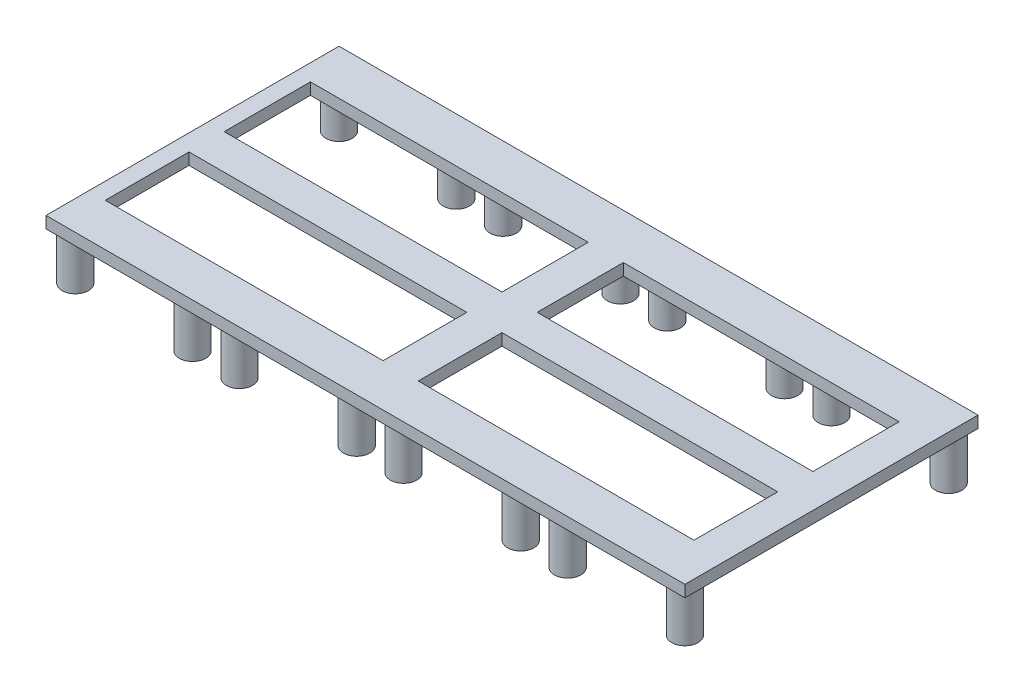
SolidWorks part; units mm, degrees
ref_plane "前视基准面" through (0, 0, 0) normal (0, 0, 1) x (1, 0, 0)
ref_plane "上视基准面" through (0, 0, 0) normal (0, 1, 0) x (1, 0, 0)
ref_plane "右视基准面" through (0, 0, 0) normal (1, 0, 0) x (0, 0, -1)
other "Configuration Table"
sketch "草图1" plane through (0, 0, 0) normal (0, 1, 0) x (1, 0, 0)
  line L1 (-14.9137, 39.4207) -> (10.0863, 39.4207)
  line L2 (-14.9137, 39.4207) -> (-14.9137, -10.5793)
  line L3 (-14.9137, -10.5793) -> (10.0863, -10.5793)
  line L4 (10.0863, 39.4207) -> (10.0863, -10.5793)
  line L5 (-14.9137, 39.4207) -> (10.0863, -10.5793) construction
  line L6 (-14.9137, -10.5793) -> (10.0863, 39.4207) construction
  line L7 (-12.4137, 36.9207) -> (7.5863, 36.9207)
  line L8 (-12.4137, 36.9207) -> (-12.4137, -8.0793)
  line L9 (-12.4137, -8.0793) -> (7.5863, -8.0793)
  line L10 (7.5863, 36.9207) -> (7.5863, -8.0793)
  line L11 (-12.4137, 36.9207) -> (7.5863, -8.0793) construction
  line L12 (-12.4137, -8.0793) -> (7.5863, 36.9207) construction
  circle A0 centre (-12.4137, 36.9207) radius 2.25
  circle A1 centre (7.5863, 36.9207) radius 2.25
  circle A2 centre (7.5863, -8.0793) radius 2.25
  circle A3 centre (-12.4137, -8.0793) radius 2.25
  circle A4 centre (-12.4137, 36.9207) radius 1.5
  circle A5 centre (7.5863, 36.9207) radius 1.5
  circle A6 centre (-12.4137, -8.0793) radius 1.5
  circle A7 centre (7.5863, -8.0793) radius 1.5
  point P0 (-2.4137, 14.4207)
  point P5 (-2.4137, 14.4207)
  dimension "D1" = 50
  dimension "D2" = 25
  dimension "D3" = 45
  dimension "D4" = 20
  dimension "D5" = 2.5
  dimension "D6" = 2.5
extrude "凸台-拉伸1" add sketch "草图1" along normal blind 2 contours A3 L9 A2 L10 A1 L7 A0 L8 | L4 L1 L2 L3 A3 L8 A0 L7 A1 L10 A2 L9 | A5 L10 A1 L7 | L10 A5 L7 | L7 A5 L10 | A5 L7 A1 L10 | A4 L7 A0 L8 | L7 A4 L8 | L8 A4 L7 | A4 L8 A0 L7 | A7 L9 A2 L10 | L9 A7 L10 | A7 L10 A2 L9 | L10 A7 L9 | L9 A6 L8 | A6 L8 A3 L9 | L8 A6 L9 | A6 L9 A3 L8
sketch "草图2" plane through (0, 0, 0) normal (0, -1, 0) x (1, 0, 0)
  line L0 (-14.9137, -39.4207) -> (-14.9137, 10.5793) construction
  line L1 (-12.4137, 8.0793) -> (7.5863, 8.0793)
  line L2 (-12.4137, 8.0793) -> (-12.4137, -36.9207)
  line L3 (-12.4137, -36.9207) -> (7.5863, -36.9207)
  line L4 (7.5863, 8.0793) -> (7.5863, -36.9207)
  line L5 (-14.9137, -39.4207) -> (10.0863, -39.4207) construction
  circle A0 centre (-12.4137, 8.0793) radius 2.25
  circle A1 centre (7.5863, 8.0793) radius 2.25
  circle A2 centre (-12.4137, -36.9207) radius 2.25
  circle A3 centre (7.5863, -36.9207) radius 2.25
  circle A4 centre (-12.4137, 8.0793) radius 1.5
  circle A5 centre (7.5863, 8.0793) radius 1.5
  circle A6 centre (7.5863, -36.9207) radius 1.5
  circle A7 centre (-12.4137, -36.9207) radius 1.5
  dimension "D1" = 45
  dimension "D2" = 20
  dimension "D3" = 2.5
  dimension "D4" = 2.5
extrude "凸台-拉伸2" add sketch "草图2" along normal blind 8 contours A4 L1 A0 L2 | A4 L2 A0 L1 | A5 L4 A1 L1 | A5 L1 A1 L4 | A7 L2 A2 L3 | A7 L3 A2 L2 | A6 L4 A3 L3 | A6 L3 A3 L4
sketch "草图4" plane through (0, 0, 0) normal (0, -1, 0) x (1, 0, 0)
  line L1 (10.0863, 10.5793) -> (38.0863, 10.5793)
  line L2 (10.0863, 10.5793) -> (10.0863, -39.4207)
  line L3 (10.0863, -39.4207) -> (38.0863, -39.4207)
  line L4 (38.0863, 10.5793) -> (38.0863, -39.4207)
  dimension "D1" = 50
  dimension "D2" = 28
extrude "凸台-拉伸3" add sketch "草图4" against normal blind 2
sketch "草图5" plane through (0, 0, 0) normal (0, -1, 0) x (1, 0, 0)
  line L1 (38.0863, 10.5793) -> (13.0863, 10.5793)
  line L2 (38.0863, 10.5793) -> (38.0863, -39.4207)
  line L3 (38.0863, -39.4207) -> (13.0863, -39.4207)
  line L4 (13.0863, 10.5793) -> (13.0863, -39.4207)
  line L5 (-14.9137, -39.4207) -> (38.0863, -39.4207) construction
  line L7 (15.5863, 8.0793) -> (35.5863, 8.0793)
  line L8 (15.5863, 8.0793) -> (15.5863, -36.9207)
  line L9 (15.5863, -36.9207) -> (35.5863, -36.9207)
  line L10 (35.5863, 8.0793) -> (35.5863, -36.9207)
  circle A0 centre (15.5863, -36.9207) radius 2.25
  circle A1 centre (35.5863, -36.9207) radius 1.5
  circle A2 centre (15.5863, 8.0793) radius 2.25
  circle A3 centre (35.5863, 8.0793) radius 2.25
  circle A4 centre (15.5863, 8.0793) radius 1.5
  circle A5 centre (35.5863, 8.0793) radius 1.3
  circle A6 centre (15.5863, -36.9207) radius 1.5
  circle A7 centre (35.5863, -36.9207) radius 2.25
  dimension "D1" = 50
  dimension "D2" = 25
  dimension "D3" = 45
  dimension "D4" = 20
  dimension "D5" = 2.5
  dimension "D6" = 2.5
extrude "凸台-拉伸4" add sketch "草图5" along normal blind 8 contours A4 L7 A2 L8 | A4 L8 A2 L7 | A5 L10 A3 L7 | A5 L7 A3 L10 | A6 L8 A0 L9 | A6 L9 A0 L8 | L9 A7 L10 A1 | L10 A7 L9 A1
sketch "草图6" plane through (0, 0, 0) normal (0, -1, 0) x (1, 0, 0)
  line L1 (38.0863, 10.5793) -> (66.0863, 10.5793)
  line L2 (38.0863, 10.5793) -> (38.0863, -39.4207)
  line L3 (38.0863, -39.4207) -> (66.0863, -39.4207)
  line L4 (66.0863, 10.5793) -> (66.0863, -39.4207)
  dimension "D1" = 50
  dimension "D2" = 28
extrude "凸台-拉伸5" add sketch "草图6" against normal blind 2
sketch "草图7" plane through (0, 0, 0) normal (0, -1, 0) x (1, 0, 0)
  line L1 (66.0863, 10.5793) -> (41.0863, 10.5793)
  line L2 (66.0863, 10.5793) -> (66.0863, -39.4207)
  line L3 (66.0863, -39.4207) -> (41.0863, -39.4207)
  line L4 (41.0863, 10.5793) -> (41.0863, -39.4207)
  line L5 (-14.9137, -39.4207) -> (66.0863, -39.4207) construction
  line L7 (43.5863, 8.0793) -> (63.5863, 8.0793)
  line L8 (43.5863, 8.0793) -> (43.5863, -36.9207)
  line L9 (43.5863, -36.9207) -> (63.5863, -36.9207)
  line L10 (63.5863, 8.0793) -> (63.5863, -36.9207)
  circle A0 centre (43.5863, 8.0793) radius 2.25
  circle A1 centre (43.5863, 8.0793) radius 1.5
  circle A2 centre (63.5863, 8.0793) radius 2.25
  circle A3 centre (63.5863, 8.0793) radius 1.5
  circle A4 centre (43.5863, -36.9207) radius 2.25
  circle A5 centre (43.5863, -36.9207) radius 1.5
  circle A7 centre (63.5863, -36.9207) radius 2.25
  circle A8 centre (63.5863, -36.9207) radius 1.5
  dimension "D1" = 50
  dimension "D2" = 25
  dimension "D3" = 45
  dimension "D4" = 20
  dimension "D5" = 2.5
  dimension "D6" = 2.5
extrude "凸台-拉伸6" add sketch "草图7" along normal blind 8 contours A1 L7 A0 L8 | A1 L8 A0 L7 | A3 L10 A2 L7 | A3 L7 A2 L10 | A5 L8 A4 L9 | A5 L9 A4 L8 | A8 L9 A7 L10 | A8 L10 A7 L9
sketch "草图8" plane through (0, 0, 0) normal (0, -1, 0) x (1, 0, 0)
  line L1 (66.0863, 10.5793) -> (94.0863, 10.5793)
  line L2 (66.0863, 10.5793) -> (66.0863, -39.4207)
  line L3 (66.0863, -39.4207) -> (94.0863, -39.4207)
  line L4 (94.0863, 10.5793) -> (94.0863, -39.4207)
  dimension "D1" = 50
  dimension "D2" = 28
extrude "凸台-拉伸7" add sketch "草图8" against normal blind 2
sketch "草图9" plane through (0, 0, 0) normal (0, -1, 0) x (1, 0, 0)
  line L1 (94.0863, 10.5793) -> (69.0863, 10.5793)
  line L2 (94.0863, 10.5793) -> (94.0863, -39.4207)
  line L3 (94.0863, -39.4207) -> (69.0863, -39.4207)
  line L4 (69.0863, 10.5793) -> (69.0863, -39.4207)
  line L5 (-14.9137, -39.4207) -> (94.0863, -39.4207) construction
  line L7 (71.5863, 8.0793) -> (91.5863, 8.0793)
  line L8 (71.5863, 8.0793) -> (71.5863, -36.9207)
  line L9 (71.5863, -36.9207) -> (91.5863, -36.9207)
  line L10 (91.5863, 8.0793) -> (91.5863, -36.9207)
  circle A0 centre (71.5863, 8.0793) radius 2.25
  circle A1 centre (71.5863, 8.0793) radius 1.5
  circle A2 centre (91.5863, 8.0793) radius 2.25
  circle A3 centre (91.5863, 8.0793) radius 1.5
  circle A4 centre (71.5863, -36.9207) radius 2.25
  circle A5 centre (71.5863, -36.9207) radius 1.5
  circle A6 centre (91.5863, -36.9207) radius 2.25
  circle A7 centre (91.5863, -36.9207) radius 1.5
  dimension "D1" = 50
  dimension "D2" = 25
  dimension "D3" = 45
  dimension "D4" = 20
  dimension "D5" = 2.5
  dimension "D6" = 2.5
extrude "凸台-拉伸8" add sketch "草图9" along normal blind 8 contours A1 L7 A0 L8 | A1 L8 A0 L7 | A3 L10 A2 L7 | A3 L7 A2 L10 | A5 L8 A4 L9 | A5 L9 A4 L8 | A7 L10 A6 L9 | A7 L9 A6 L10
sketch "草图10" plane through (0, 0, 0) normal (0, -1, 0) x (1, 0, 0)
  line L1 (-14.9137, 5.7915) -> (94.0863, 5.7915)
  line L2 (-14.9137, 5.7915) -> (-14.9137, -34.2085)
  line L3 (-14.9137, -34.2085) -> (94.0863, -34.2085)
  line L4 (94.0863, 5.7915) -> (94.0863, -34.2085)
  line L6 (-14.9137, -39.4207) -> (-14.9137, 10.5793) construction
  line L7 (94.0863, -39.4207) -> (94.0863, 10.5793) construction
  line L9 (-12.0912, 3.2915) -> (88.3449, 3.2915)
  line L10 (-12.0912, 3.2915) -> (-12.0912, -31.7085)
  line L11 (-12.0912, -31.7085) -> (88.3449, -31.7085)
  line L12 (88.3449, 3.2915) -> (88.3449, -31.7085)
  line L13 (35.298, 3.2915) -> (41.298, 3.2915)
  line L14 (35.298, 3.2915) -> (35.298, -31.7085)
  line L15 (35.298, -31.7085) -> (41.298, -31.7085)
  line L16 (41.298, 3.2915) -> (41.298, -31.7085)
  line L17 (-12.0912, -10.997) -> (88.3449, -10.997)
  line L18 (-12.0912, -10.997) -> (-12.0912, -16.997)
  line L19 (-12.0912, -16.997) -> (88.3449, -16.997)
  line L20 (88.3449, -10.997) -> (88.3449, -16.997)
  dimension "D1" = 40
  dimension "D2" = 109
  dimension "D3" = 35
  dimension "D4" = 100.436
  dimension "D5" = 2.5
  dimension "D6" = 35
  dimension "D7" = 6
  dimension "D8" = 6
  dimension "D9" = 100.436
extrude "切除-拉伸1" cut sketch "草图10" against normal blind 2 contours L19 L16 L11 L12 | L19 L10 L11 L14 | L16 L17 L12 L9 | L10 L17 L14 L9
